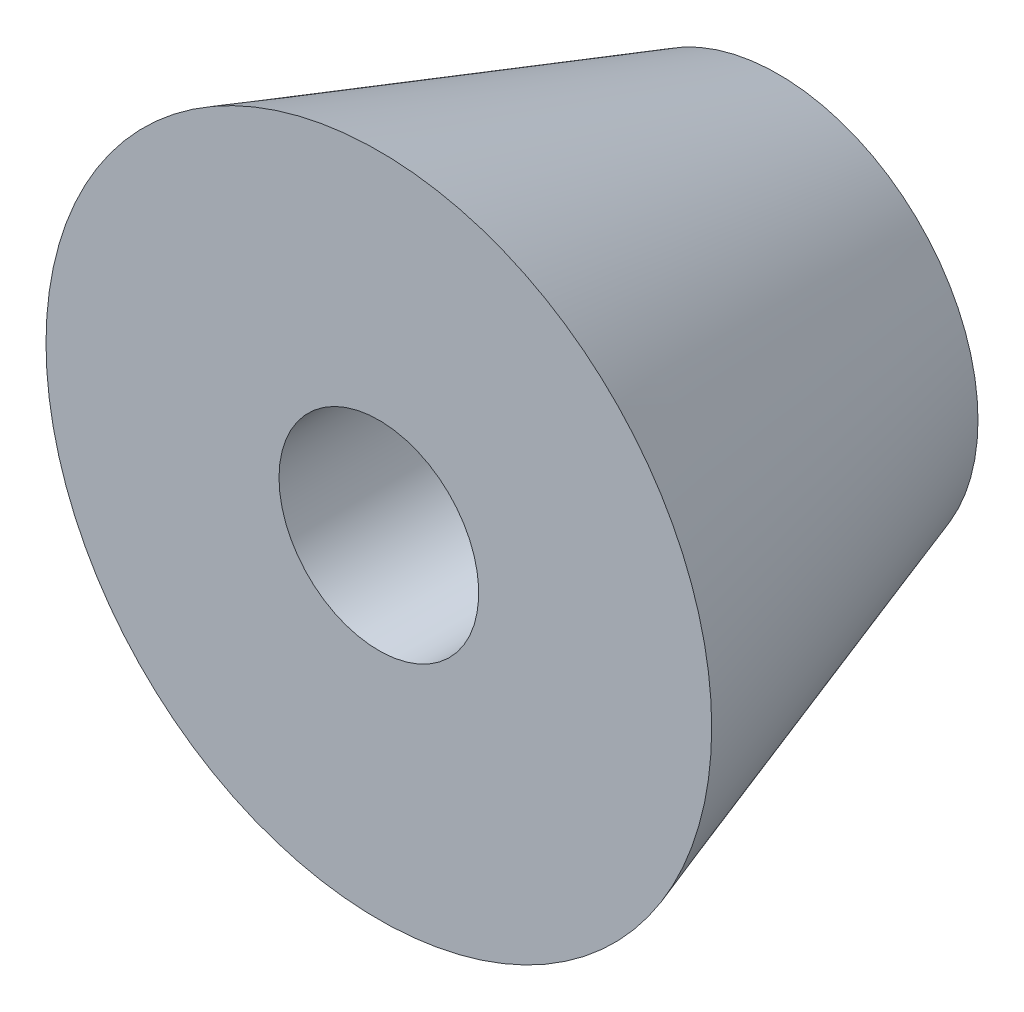
SolidWorks part; units mm, degrees
material "BUTYL"
ref_plane "前视基准面" through (0, 0, 0) normal (0, 0, 1) x (1, 0, 0)
ref_plane "上视基准面" through (0, 0, 0) normal (0, 1, 0) x (1, 0, 0)
ref_plane "右视基准面" through (0, 0, 0) normal (1, 0, 0) x (0, 0, -1)
other "Configuration Table"
sketch "草图1" plane through (0, 0, 0) normal (0, 1, 0) x (1, 0, 0)
  line L0 (0, 15.6667) -> (0, -15.6667) construction
  line L1 (-3, -0.6889) -> (0, -0.6889)
  line L2 (0, -0.6889) -> (0, -6.6889)
  line L3 (0, -6.6889) -> (-5, -6.6889)
  line L4 (-5, -6.6889) -> (-3, -0.6889)
  line L6 (0, -0.6889) -> (-1.5, -0.6889)
  line L7 (0, -0.6889) -> (0, -6.6889)
  line L8 (0, -6.6889) -> (-1.5, -6.6889)
  line L9 (-1.5, -0.6889) -> (-1.5, -6.6889)
  point P4 (0, 0)
  dimension "D1" = 3
  dimension "D2" = 5
  dimension "D3" = 6
  dimension "D4" = 1.5
revolve "旋转2" add sketch "草图1" angle 360 about L0
